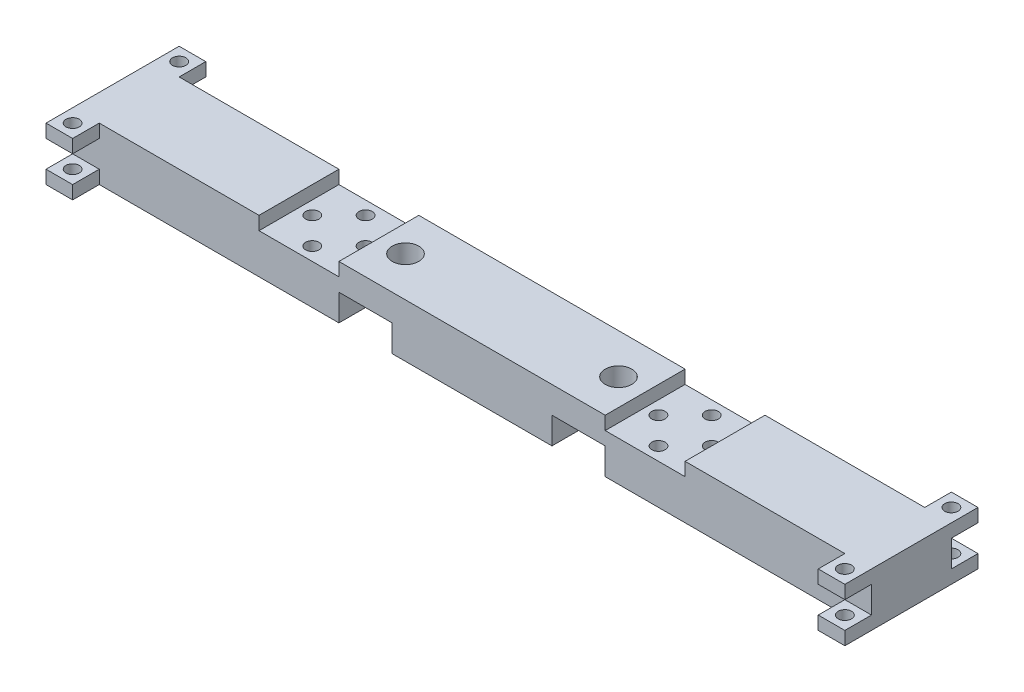
SolidWorks part; units mm, degrees
ref_plane "Front Plane" through (0, 0, 0) normal (0, 0, 1) x (1, 0, 0)
ref_plane "Top Plane" through (0, 0, 0) normal (0, 1, 0) x (1, 0, 0)
ref_plane "Right Plane" through (0, 0, 0) normal (1, 0, 0) x (0, 0, -1)
sketch "Sketch1" plane through (0, 0, 0) normal (0, 1, 0) x (1, 0, 0)
  line L0 (0, -55) -> (0, 55) construction
  line L1 (-150, -15) -> (150, -15)
  line L2 (-150, -15) -> (-150, 15)
  line L3 (-150, 15) -> (150, 15)
  line L4 (150, -15) -> (150, 15)
  line L5 (-150, -15) -> (150, 15) construction
  line L6 (-150, 15) -> (150, -15) construction
  line L7 (-150, 15) -> (-140, 15)
  line L8 (-150, 15) -> (-150, 25)
  line L9 (-150, 25) -> (-140, 25)
  line L10 (-140, 15) -> (-140, 25)
  line L11 (150, 15) -> (150, 25)
  line L12 (140, 15) -> (140, 25)
  line L13 (150, 25) -> (140, 25)
  line L14 (-55, 0) -> (55, 0) construction
  line L15 (150, -15) -> (150, -25)
  line L16 (150, -25) -> (140, -25)
  line L17 (140, -15) -> (140, -25)
  line L18 (-140, -15) -> (-140, -25)
  line L19 (-150, -25) -> (-140, -25)
  line L20 (-150, -15) -> (-150, -25)
  point P0 (0, 0)
  dimension "D1" = 300
  dimension "D2" = 30
  dimension "D3" = 10
  dimension "D4" = 10
extrude "Boss-Extrude1" add sketch "Sketch1" against normal blind 20 contours L1 L4 L3 L2 | L1 L20 L19 L18 | L3 L10 L9 L8 | L11 L13 L12 L3 | L1 L17 L16 L15
sketch "Sketch12" plane through (0, 0, 25) normal (0, 0, 1) x (1, 0, 0)
  line L0 (-150, -20) -> (-150, 0) construction
  line L1 (-150, -5) -> (-140, -5)
  line L2 (-150, -5) -> (-150, -15)
  line L3 (-150, -15) -> (-140, -15)
  line L4 (-140, -5) -> (-140, -15)
  line L5 (-140, -20) -> (-140, 0) construction
  line L6 (-150, 0) -> (-140, 0) construction
  line L7 (0, -11) -> (0, 11) construction
  line L8 (140, -5) -> (140, -15)
  line L9 (150, -15) -> (140, -15)
  line L10 (150, -5) -> (150, -15)
  line L11 (150, -5) -> (140, -5)
  dimension "D1" = 5
  dimension "D2" = 10
extrude "Cut-Extrude5" cut sketch "Sketch12" against normal up to surface (10 mm away) up to face at (0, -10, 15)
sketch "Sketch14" plane through (0, 0, -25) normal (0, 0, -1) x (-1, 0, 0)
  line L0 (-140, -20) -> (-140, 0) construction
  line L1 (-150, -5) -> (-140, -5)
  line L2 (-150, -5) -> (-150, -15)
  line L3 (-150, -15) -> (-140, -15)
  line L4 (-140, -5) -> (-140, -15)
  line L6 (0, 11) -> (0, -11) construction
  line L7 (140, -5) -> (140, -15)
  line L8 (150, -15) -> (140, -15)
  line L9 (150, -5) -> (150, -15)
  line L10 (150, -5) -> (140, -5)
  dimension "D1" = 10
extrude "Cut-Extrude6" cut sketch "Sketch14" against normal up to surface (10 mm away) up to face at (0, -10, -15)
sketch "Sketch3" plane through (0, -20, 0) normal (0, -1, 0) x (1, 0, 0)
  line L0 (-150, 25) -> (-150, -25) construction
  line L1 (-50, 15) -> (-30, 15)
  line L2 (-50, 15) -> (-50, -15)
  line L3 (-50, -15) -> (-30, -15)
  line L4 (-30, 15) -> (-30, -15)
  line L5 (-50, 15) -> (-30, -15) construction
  line L6 (-50, -15) -> (-30, 15) construction
  line L7 (0, -11) -> (0, 11) construction
  line L8 (50, -15) -> (30, -15)
  line L9 (30, 15) -> (30, -15)
  line L10 (50, 15) -> (30, 15)
  line L11 (50, 15) -> (50, -15)
  line L12 (50, -15) -> (30, 15) construction
  line L13 (50, 15) -> (30, -15) construction
  line L17 (-140, 15) -> (140, 15) construction
  line L18 (-140, -15) -> (140, -15) construction
  point P0 (-40, 0)
  point P13 (40, 0)
  dimension "D1" = 20
  dimension "D2" = 100
extrude "Cut-Extrude1" cut sketch "Sketch3" against normal blind 10
sketch "Sketch5" plane through (0, 0, 0) normal (0, 1, 0) x (1, 0, 0)
  line L0 (-11, 0) -> (11, 0) construction
  line L1 (0, -11) -> (0, 11) construction
  line L4 (150, -25) -> (140, -25) construction
  line L5 (150, -25) -> (150, 25) construction
  circle A0 centre (145, -20) radius 2.5
  circle A1 centre (145, 20) radius 2.5
  circle A2 centre (-145, 20) radius 2.5
  circle A3 centre (-145, -20) radius 2.5
  dimension "D1" = 5
  dimension "D2" = 5
  dimension "D3" = 5
extrude "Cut-Extrude3" cut sketch "Sketch5" against normal through all
sketch "Sketch7" plane through (0, -10, 0) normal (0, -1, 0) x (1, 0, 0)
  line L0 (0, -11) -> (0, 11) construction
  line L1 (-30, -15) -> (-30, 15) construction
  line L2 (-50, -15) -> (-30, -15) construction
  circle A0 centre (-40, 0) radius 5
  circle A1 centre (40, 0) radius 5
  dimension "D1" = 10
  dimension "D2" = 10
  dimension "D3" = 15
extrude "Cut-Extrude4" cut sketch "Sketch7" against normal up to next
sketch "Sketch15" plane through (0, 0, 0) normal (0, 1, 0) x (1, 0, 0)
  line L0 (-140, -15) -> (140, -15) construction
  line L1 (-50, -15) -> (-80, -15)
  line L2 (-50, -15) -> (-50, 15)
  line L3 (-50, 15) -> (-80, 15)
  line L4 (-80, -15) -> (-80, 15)
  line L5 (-140, 15) -> (140, 15) construction
  line L6 (-150, -25) -> (-150, 25) construction
  dimension "D1" = 100
  dimension "D2" = 30
extrude "Cut-Extrude7" cut sketch "Sketch15" against normal blind 5
mirror "Mirror1" about plane through (0, 0, 0) normal (1, 0, 0) of "Cut-Extrude7"
sketch "Sketch16" plane through (0, -5, 0) normal (0, 1, 0) x (1, 0, 0)
  line L5 (-50, 15) -> (-80, 15) construction
  line L6 (-80, -15) -> (-50, -15) construction
  line L7 (-50, -15) -> (-50, 15) construction
  line L8 (-80, 15) -> (-80, -15) construction
  circle A4 centre (-65, 10) radius 2.5
  circle A5 centre (-75, 0) radius 2.5
  circle A6 centre (-65, -10) radius 2.5
  circle A7 centre (-55, 0) radius 2.5
  point P8 (0, 0)
  point P9 (0, 0)
  point P10 (0, 0)
  dimension "D1" = 5
  dimension "D2" = 5
  dimension "D3" = 5
  dimension "D4" = 15
  dimension "D5" = 5
  dimension "D6" = 5
  dimension "D7" = 15
extrude "Cut-Extrude8" cut sketch "Sketch16" against normal blind 5
mirror "Mirror2" about plane through (0, 0, 0) normal (1, 0, 0) of "Cut-Extrude8"
